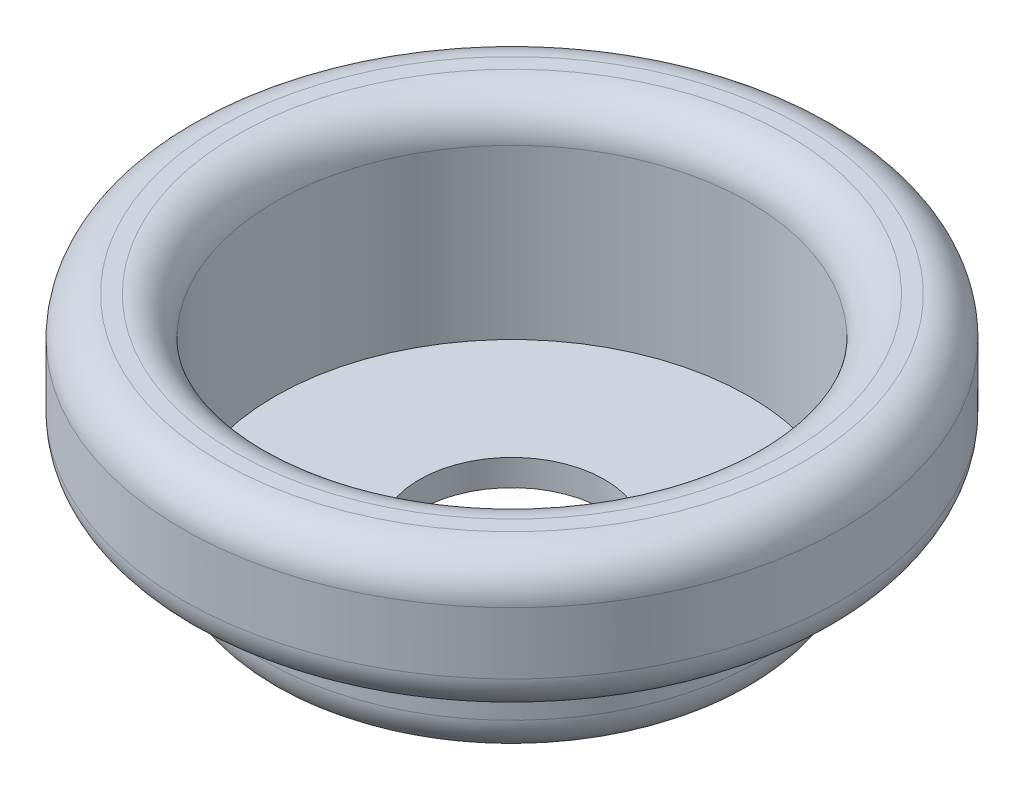
SolidWorks part; units mm, degrees
material "Brass"
ref_plane "Front Plane" through (0, 0, 0) normal (0, 0, 1) x (1, 0, 0)
ref_plane "Top Plane" through (0, 0, 0) normal (0, 1, 0) x (1, 0, 0)
ref_plane "Right Plane" through (0, 0, 0) normal (1, 0, 0) x (0, 0, -1)
sketch "Sketch1" plane through (0, 0, 0) normal (0, 0, 1) x (1, 0, 0)
  line L0 (0, 0) -> (0, 45.1745) construction
  line L1 (-4.064, 0) -> (-1.524, 0)
  line L2 (-1.524, 0) -> (-1.524, 0.4318)
  line L3 (-1.524, 0.4318) -> (-3.8989, 0.4318)
  line L4 (-3.8989, 0.4318) -> (-3.8989, 3.8354)
  line L5 (-3.8989, 3.8354) -> (-5.4229, 3.8354)
  line L6 (-5.4229, 3.8354) -> (-5.4229, 1.5494)
  line L7 (-5.4229, 1.5494) -> (-4.064, 1.5494)
  line L8 (-4.064, 1.5494) -> (-4.064, 0)
  dimension "D1" = 3.048
  dimension "D2" = 8.128
  dimension "D3" = 10.8458
  dimension "D4" = 3.8354
  dimension "D5" = 2.286
  dimension "D6" = 3.4036
  dimension "D7" = 1.524
revolve "Revolve1" add sketch "Sketch1" angle 360 about L0
fillet "Fillet1" radius 0.635 5 edges at (0, 0, -4.064) (0, 1.5494, -4.064) (0, 1.5494, -5.4229) (0, 3.8354, -5.4229) (0, 3.8354, -3.8989)
